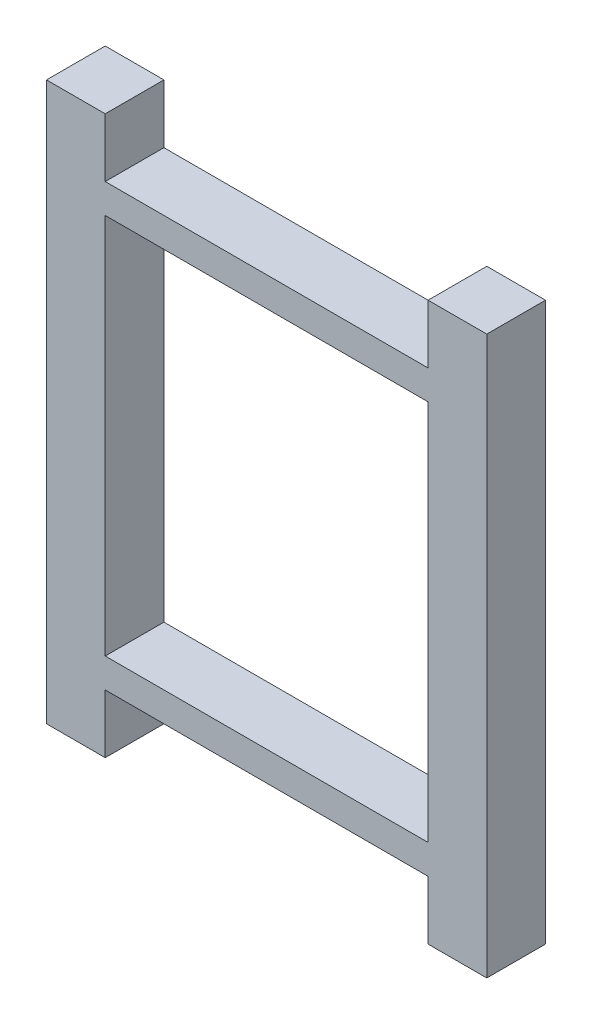
SolidWorks part; units mm, degrees
ref_plane "Front" through (0, 0, 0) normal (0, 0, 1) x (1, 0, 0)
ref_plane "Top" through (0, 0, 0) normal (0, 1, 0) x (1, 0, 0)
ref_plane "Right" through (0, 0, 0) normal (1, 0, 0) x (0, 0, -1)
sketch "Sketch2" plane through (0, 0, 0) normal (0, 0, 1) x (1, 0, 0)
  line L0 (0, 51) -> (-45, 51) construction
  line L1 (0, 0) -> (-45, 0)
  line L2 (0, 0) -> (0, 57)
  line L3 (0, 57) -> (-45, 57)
  line L4 (-45, 0) -> (-45, 57)
  line L5 (0, 6) -> (-45, 6) construction
  line L6 (-39, 0) -> (-39, 57) construction
  line L7 (-6, 0) -> (-6, 57) construction
  line L8 (0, 48) -> (-45, 48) construction
  line L9 (0, 9) -> (-45, 9) construction
  line L10 (-39, 51) -> (-39, 57)
  line L11 (-39, 48) -> (-6, 48)
  line L12 (-39, 48) -> (-39, 9)
  line L13 (-39, 9) -> (-6, 9)
  line L14 (-6, 48) -> (-6, 9)
  line L15 (-39, 51) -> (-6, 51)
  line L16 (-6, 51) -> (-6, 57)
  line L17 (-6, 0) -> (-6, 6)
  line L18 (-6, 6) -> (-39, 6)
  line L19 (-39, 6) -> (-39, 0)
  dimension "D1" = 57
  dimension "D2" = 45
  dimension "D3" = 6
  dimension "D4" = 6
  dimension "D5" = 6
  dimension "D6" = 6
  dimension "D7" = 3
  dimension "D8" = 3
extrude "Boss-Extrude1" add sketch "Sketch2" along normal blind 6 contours L19 L18 L17 L1 L2 L3 L16 L15 L10 L4 L11 L14 L13 L12
